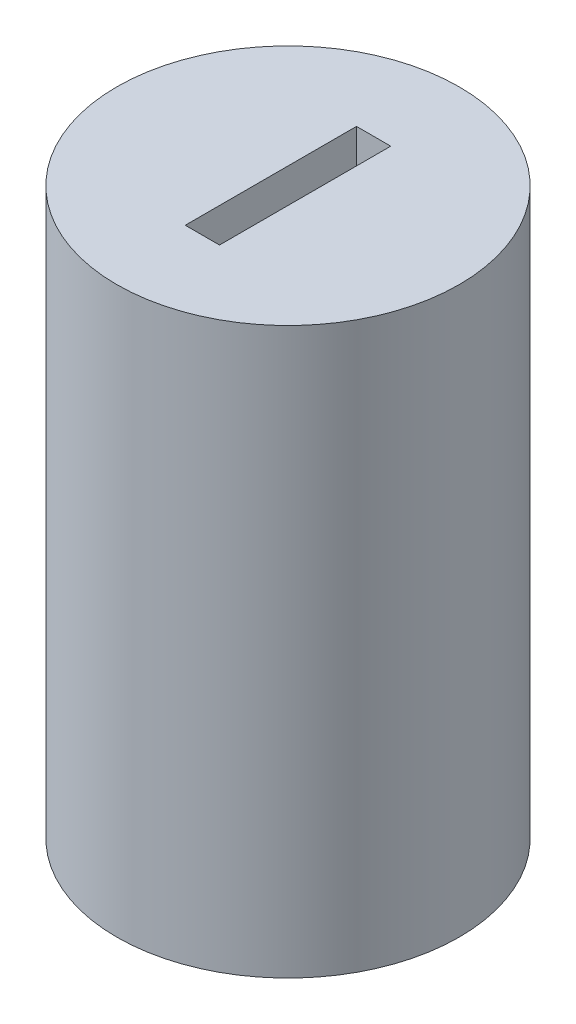
SolidWorks part; units mm, degrees
ref_plane "Plano frontal" through (0, 0, 0) normal (0, 0, 1) x (1, 0, 0)
ref_plane "Plano superior" through (0, 0, 0) normal (0, 1, 0) x (1, 0, 0)
ref_plane "Plano direito" through (0, 0, 0) normal (1, 0, 0) x (0, 0, -1)
sketch "Esboço1" plane through (0, 0, 0) normal (0, 1, 0) x (1, 0, 0)
  circle A0 centre (0, 0) radius 5
  dimension "D1" = 10
sketch "Esboço2" plane through (0, 0, 0) normal (0, 1, 0) x (1, 0, 0)
extrude "Ressalto-extrusão1" add sketch "Esboço1" along normal blind 1
ref_plane "Plano1" through (0, 0.5, 0) normal (0, 1, 0) x (1, 0, 0)
sketch "Esboço3" plane through (0, 0.5, 0) normal (0, 1, 0) x (1, 0, 0)
  circle A0 centre (0, 0) radius 5
  dimension "D1" = 10
extrude "Ressalto-extrusão3" add sketch "Esboço3" along normal blind 15
sketch "Esboço4" plane through (0, 15.5, 0) normal (0, 1, 0) x (1, 0, 0)
  circle A0 centre (0, 0) radius 4.75
  point P0 (0, 0)
  dimension "D1" = 9.5
extrude "Corte-extrusão2" cut sketch "Esboço4" against normal up to surface (15 mm away)
ref_plane "Plano2" through (0, 15.5, 0) normal (0, 1, 0) x (1, 0, 0)
sketch "Esboço5" plane through (0, 15.5, 0) normal (0, 1, 0) x (1, 0, 0)
  circle A0 centre (0, 0) radius 5
extrude "Ressalto-extrusão4" add sketch "Esboço5" along normal blind 1
sketch "Esboço6" plane through (0, 16.5, 0) normal (0, 1, 0) x (1, 0, 0)
  line L1 (-0.5, 2.5) -> (0.5, 2.5)
  line L2 (-0.5, 2.5) -> (-0.5, -2.5)
  line L3 (-0.5, -2.5) -> (0.5, -2.5)
  line L4 (0.5, 2.5) -> (0.5, -2.5)
  line L5 (-0.5, 2.5) -> (0.5, -2.5) construction
  line L6 (-0.5, -2.5) -> (0.5, 2.5) construction
  point P0 (0, 0)
  point P8 (-0.5, 2.4368)
  dimension "D1" = 1
  dimension "D2" = 5
extrude "Corte-extrusão3" cut sketch "Esboço6" against normal blind 1
